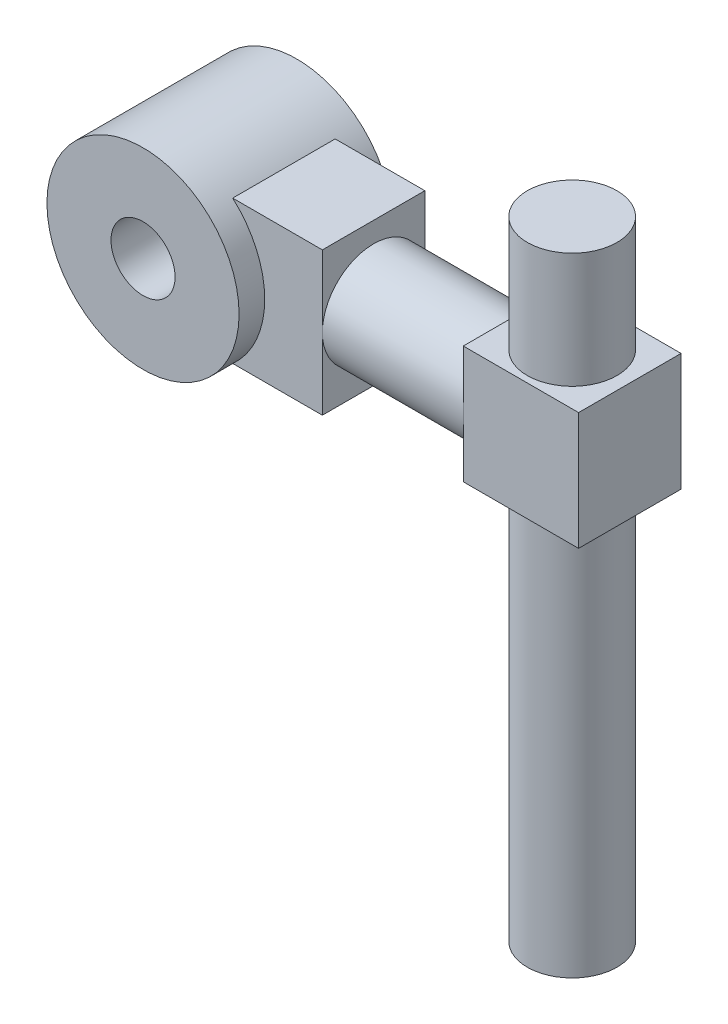
SolidWorks part; units mm, degrees
ref_plane "Front Plane" through (0, 0, 0) normal (0, 0, 1) x (1, 0, 0)
ref_plane "Top Plane" through (0, 0, 0) normal (0, 1, 0) x (1, 0, 0)
ref_plane "Right Plane" through (0, 0, 0) normal (1, 0, 0) x (0, 0, -1)
sketch "Sketch1" plane through (0, 0, 0) normal (0, 0, 1) x (1, 0, 0)
  circle A0 centre (0, 0) radius 12.5
  circle A1 centre (0, 0) radius 37.5
  dimension "D1" = 25
  dimension "D2" = 75
extrude "Boss-Extrude1" add sketch "Sketch1" along normal blind 10
sketch "Sketch2" plane through (0, 0, 10) normal (0, 0, 1) x (1, 0, 0)
  line L0 (25, 27.9508) -> (25, -27.9508)
  circle A0 centre (0, 0) radius 37.5 construction
  circle A5 centre (0, 0) radius 12.5
  arc A6 (25, 27.9508) -> (25, -27.9508) centre (0, 0) ccw
  dimension "D1" = 25
  dimension "D2" = 25
extrude "Boss-Extrude2" add sketch "Sketch2" along normal blind 40
sketch "Sketch3" plane through (0, 0, 50) normal (0, 0, 1) x (1, 0, 0)
  circle A0 centre (0, 0) radius 12.5
  circle A2 centre (0, 0) radius 37.5
extrude "Boss-Extrude3" add sketch "Sketch3" along normal blind 10
sketch "Sketch4" plane through (25, 0, 0) normal (1, 0, 0) x (0, 0, -1)
  line L1 (-50, 27.9508) -> (-10, 27.9508)
  line L2 (-50, 27.9508) -> (-50, -27.9508)
  line L3 (-50, -27.9508) -> (-10, -27.9508)
  line L4 (-10, 27.9508) -> (-10, -27.9508)
extrude "Boss-Extrude4" add sketch "Sketch4" along normal blind 35
sketch "Sketch5" plane through (60, 0, 0) normal (1, 0, 0) x (0, 0, -1)
  line L0 (-50, 27.9508) -> (-10, -27.9508) construction
  line L1 (-10, 27.9508) -> (-50, -27.9508) construction
  circle A0 centre (-30, 0) radius 20
  dimension "D1" = 40
extrude "Boss-Extrude5" add sketch "Sketch5" along normal blind 55
sketch "Sketch6" plane through (115, 0, 0) normal (1, 0, 0) x (0, 0, -1)
  line L0 (-50, 27.9508) -> (-50, -27.9508) construction
  line L1 (-50, 22.9508) -> (-10, 22.9508)
  line L2 (-50, 22.9508) -> (-50, -22.9508)
  line L3 (-50, -22.9508) -> (-10, -22.9508)
  line L4 (-10, 22.9508) -> (-10, -22.9508)
  line L5 (-10, -27.9508) -> (-10, 27.9508) construction
  line L6 (-10, 27.9508) -> (-50, 27.9508) construction
  line L7 (-50, -27.9508) -> (-10, -27.9508) construction
  dimension "D1" = 5
  dimension "D2" = 5
extrude "Boss-Extrude6" add sketch "Sketch6" along normal blind 45
sketch "Sketch7" plane through (0, 22.9508, 0) normal (0, 1, 0) x (1, 0, 0)
  line L0 (115, -10) -> (160, -50) construction
  line L1 (160, -10) -> (115, -50) construction
  circle A0 centre (137.5, -30) radius 17.5
  dimension "D1" = 35
extrude "Boss-Extrude7" add sketch "Sketch7" along normal blind 45 and the other way blind 200
